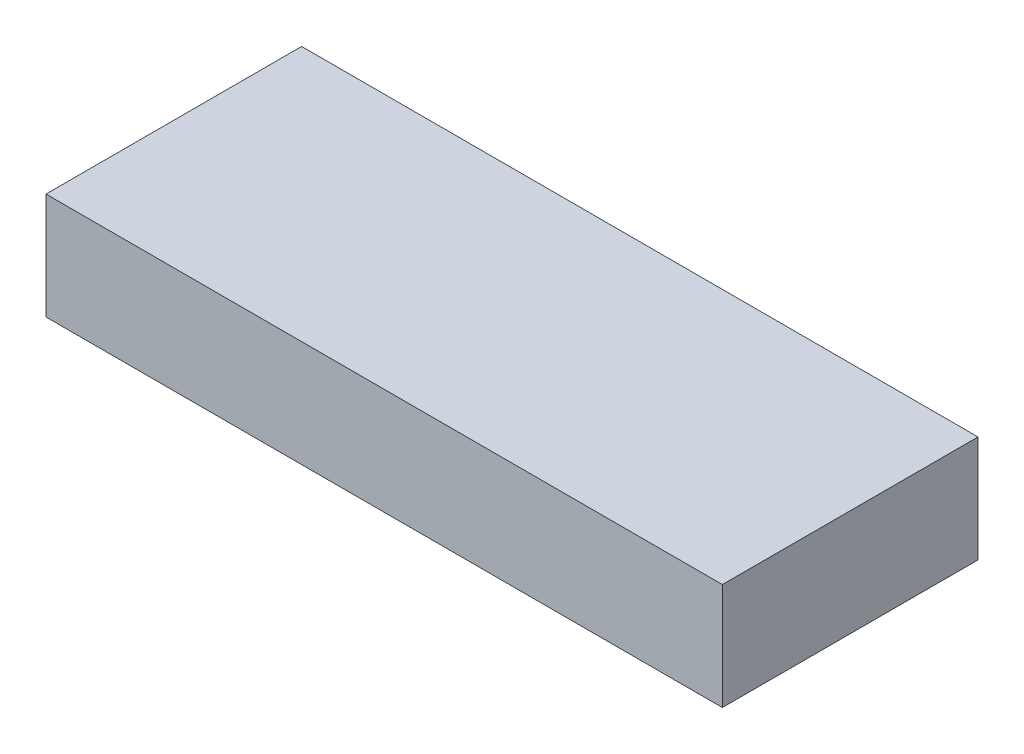
SolidWorks part; units mm, degrees
ref_plane "Спереди" through (0, 0, 0) normal (0, 0, 1) x (1, 0, 0)
ref_plane "Сверху" through (0, 0, 0) normal (0, 1, 0) x (1, 0, 0)
ref_plane "Справа" through (0, 0, 0) normal (1, 0, 0) x (0, 0, -1)
sketch "Эскиз1" plane through (0, 0, 0) normal (0, 1, 0) x (1, 0, 0)
  line L1 (0, 0) -> (50.8, 0)
  line L2 (0, 0) -> (0, -19.2)
  line L3 (0, -19.2) -> (50.8, -19.2)
  line L4 (50.8, 0) -> (50.8, -19.2)
  dimension "D1" = 50.8
  dimension "D2" = 19.2
extrude "Бобышка-Вытянуть1" add sketch "Эскиз1" along normal blind 8
